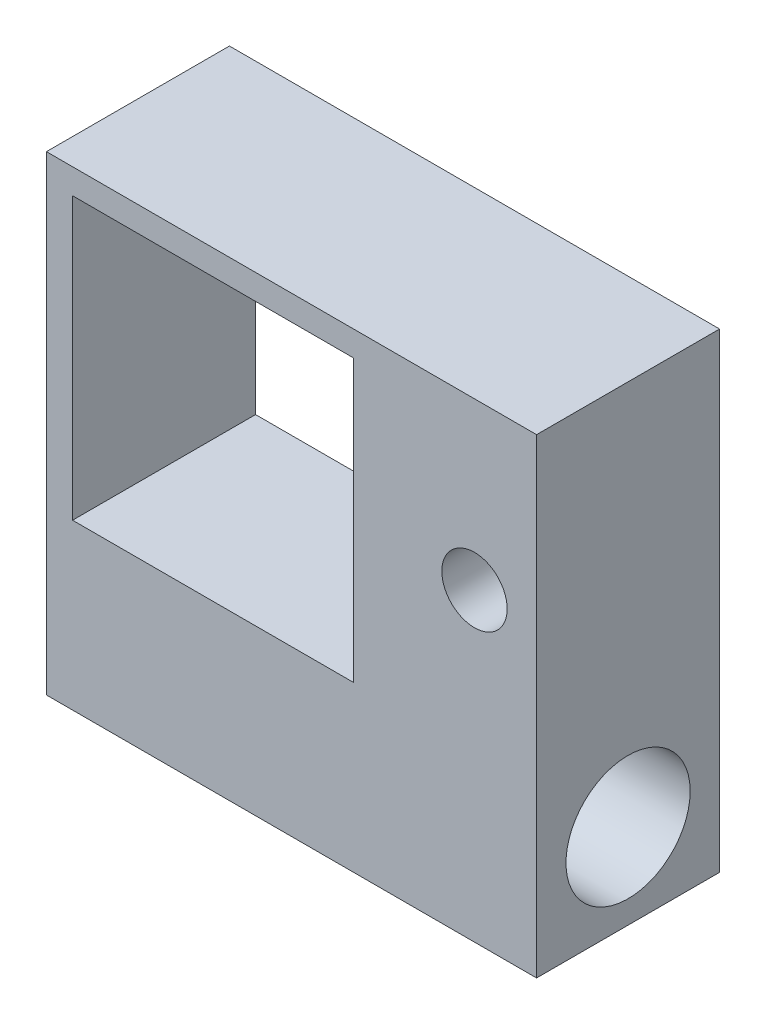
SolidWorks part; units mm, degrees
ref_plane "Front Plane" through (0, 0, 0) normal (0, 0, 1) x (1, 0, 0)
ref_plane "Top Plane" through (0, 0, 0) normal (0, 1, 0) x (1, 0, 0)
ref_plane "Right Plane" through (0, 0, 0) normal (1, 0, 0) x (0, 0, -1)
sketch "Sketch1" plane through (0, 0, 0) normal (0, 0, 1) x (1, 0, 0)
  line L0 (9.5, 32.16) -> (-33.5, -10.84) construction
  line L1 (-37.5, -36) -> (37.5, -36)
  line L2 (-37.5, -36) -> (-37.5, 36)
  line L3 (-37.5, 36) -> (37.5, 36)
  line L4 (37.5, -36) -> (37.5, 36)
  line L5 (-37.5, -36) -> (37.5, 36) construction
  line L6 (-37.5, 36) -> (37.5, -36) construction
  line L7 (-33.5, 32.16) -> (9.5, 32.16)
  line L8 (-33.5, 32.16) -> (-33.5, -10.84)
  line L9 (-33.5, -10.84) -> (9.5, -10.84)
  line L10 (9.5, 32.16) -> (9.5, -10.84)
  line L11 (-33.5, 32.16) -> (9.5, -10.84) construction
  circle A0 centre (28, 10.66) radius 5
  point P0 (0, 0)
  point P12 (9.5, 10.66)
  point P13 (-12, 10.66)
  dimension "D3" = 10
  dimension "D7" = 9.5
  dimension "D1" = 75
  dimension "D2" = 72
  dimension "D4" = 43
  dimension "D5" = 4
  dimension "D8" = 0
  dimension "D9" = 3.84
  dimension "D10" = 40
  dimension "D11" = 43
extrude "Boss-Extrude1" add sketch "Sketch1" along normal blind 28
sketch "Sketch2" plane through (37.5, 0, 0) normal (1, 0, 0) x (0, 0, -1)
  line L0 (-28, -36) -> (0, -36) construction
  circle A0 centre (-14, -23) radius 9.5
  dimension "D1" = 19
  dimension "D2" = 13
extrude "Cut-Extrude1" cut sketch "Sketch2" against normal through all
